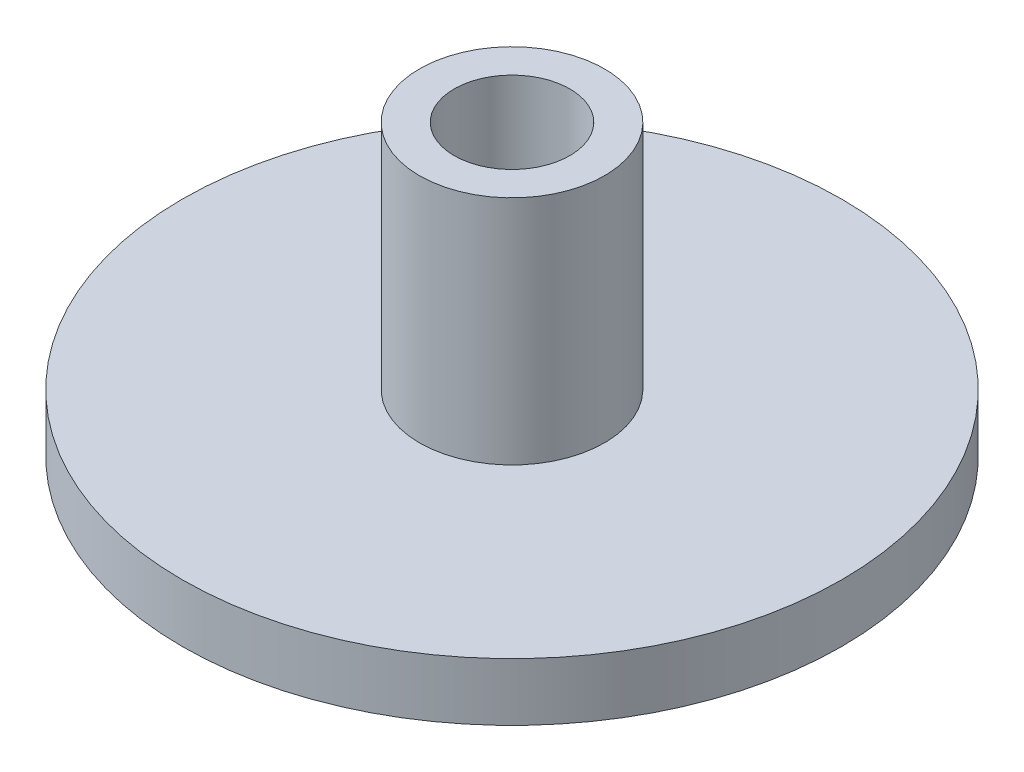
SolidWorks part; units mm, degrees
ref_plane "Front Plane" through (0, 0, 0) normal (0, 0, 1) x (1, 0, 0)
ref_plane "Top Plane" through (0, 0, 0) normal (0, 1, 0) x (1, 0, 0)
ref_plane "Right Plane" through (0, 0, 0) normal (1, 0, 0) x (0, 0, -1)
sketch "Sketch1" plane through (0, 0, 0) normal (0, 1, 0) x (1, 0, 0)
  circle A0 centre (0, 0) radius 28.5
extrude "Boss-Extrude1" add sketch "Sketch1" along normal blind 5
sketch "Sketch2" plane through (0, 5, 0) normal (0, 1, 0) x (1, 0, 0)
  circle A0 centre (0, 0) radius 8
extrude "Boss-Extrude2" add sketch "Sketch2" along normal blind 20
sketch "Sketch3" plane through (0, 25, 0) normal (0, 1, 0) x (1, 0, 0)
  circle A0 centre (0, 0) radius 5
extrude "Cut-Extrude1" cut sketch "Sketch3" against normal through all
